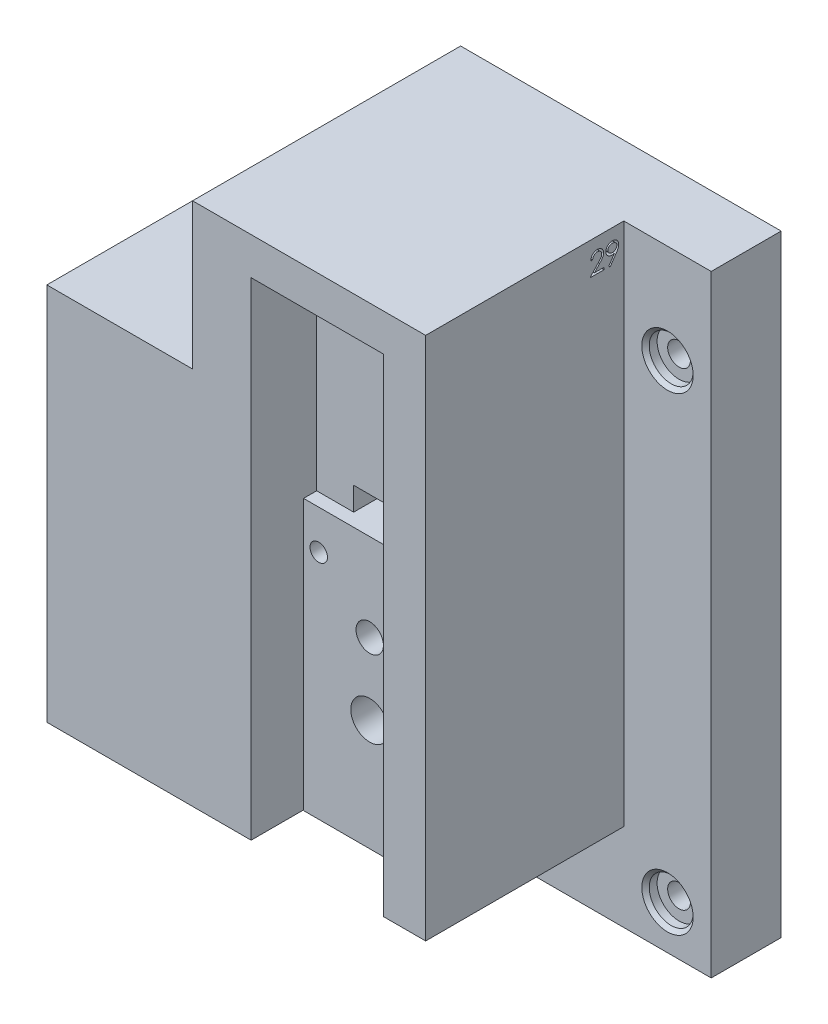
SolidWorks part; units mm, degrees
ref_plane "Front Plane" through (0, 0, 0) normal (0, 0, 1) x (1, 0, 0)
ref_plane "Top Plane" through (0, 0, 0) normal (0, 1, 0) x (1, 0, 0)
ref_plane "Right Plane" through (0, 0, 0) normal (1, 0, 0) x (0, 0, -1)
sketch "Sketch1" plane through (0, 0, 0) normal (0, 0, 1) x (1, 0, 0)
  line L1 (0, 0) -> (-65, 0)
  line L2 (0, 0) -> (0, -85)
  line L3 (0, -85) -> (-65, -85)
  line L4 (-65, 0) -> (-65, -85)
  dimension "D1" = 65
  dimension "D2" = 85
extrude "Boss-Extrude1" add sketch "Sketch1" along normal blind 46
sketch "Sketch2" plane through (0, 0, 46) normal (0, 0, 1) x (1, 0, 0)
  line L1 (-65, 0) -> (-40, 0)
  line L2 (-65, 0) -> (-65, -20)
  line L3 (-65, -20) -> (-40, -20)
  line L4 (-40, 0) -> (-40, -20)
  dimension "D1" = 25
  dimension "D2" = 20
extrude "Cut-Extrude1" cut sketch "Sketch2" against normal blind 46
sketch "Sketch3" plane through (0, 0, 0) normal (0, 0, -1) x (-1, 0, 0)
  line L0 (0, 0) -> (-12.6927, 0) construction
  line L1 (7.25, -1.4) -> (29.95, -1.4)
  line L2 (7.25, -1.4) -> (7.25, -83.6)
  line L3 (7.25, -83.6) -> (29.95, -83.6)
  line L4 (29.95, -1.4) -> (29.95, -83.6)
  line L5 (0, -85) -> (-40.2138, -85) construction
  line L7 (0, 0) -> (0, 18.8306) construction
  line L8 (40, 0) -> (40, 20.415) construction
  dimension "D1" = 22.7
  dimension "D2" = 82.2
  dimension "D3" = 2.8
  dimension "D4" = 14.5
extrude "Cut-Extrude2" cut sketch "Sketch3" against normal blind 43.2
sketch "Sketch4" plane through (0, 0, 43.2) normal (0, 0, -1) x (-1, 0, 0)
  line L0 (7.25, -83.6) -> (29.95, -83.6) construction
  line L1 (32.75, -1.4) -> (32.75, 6.5075) construction
  line L2 (32.75, -1.4) -> (54.2037, -1.4) construction
  line L3 (20, -65.9) -> (20, -109.1767) construction
  line L6 (7.25, -1.4) -> (7.25, -83.6) construction
  line L7 (11.25, -21.4049) -> (11.25, -31.9502) construction
  line L8 (7.25, -1.4) -> (7.25, -83.6) construction
  line L11 (25.95, -17.2988) -> (25.95, -39.3226) construction
  line L12 (29.95, -83.6) -> (29.95, -1.4) construction
  line L13 (7.25, -83.6) -> (-10.7411, -83.6) construction
  line L14 (7.25, -1.4) -> (7.25, 5.7136) construction
  line L15 (16.5, -29.53) -> (23.5, -29.53)
  line L16 (16.5, -29.53) -> (16.5, -34.33)
  line L17 (16.5, -34.33) -> (23.5, -34.33)
  line L18 (23.5, -29.53) -> (23.5, -34.33)
  circle A0 centre (20, -65.9) radius 3.25
  circle A1 centre (20, -53.6) radius 2.35
  circle A2 centre (11.25, -45.3) radius 1.5
  circle A3 centre (25.95, -45.3) radius 1.5
  point P4 (18.6, -83.6)
  dimension "D2" = 6.5
  dimension "D4" = 4.7
  dimension "D3" = 12.75
  dimension "D9" = 38.3
  dimension "D10" = 3
  dimension "D11" = 3
  dimension "D1" = 17.7
  dimension "D5" = 30
  dimension "D6" = 4
  dimension "D7" = 4
  dimension "D8" = 38.3
  dimension "D12" = 4.8
  dimension "D13" = 7
  dimension "D14" = 28.13
  dimension "D15" = 3.5
extrude "Cut-Extrude3" cut sketch "Sketch4" against normal blind 29
sketch "Sketch5" plane through (0, 0, 43.2) normal (0, 0, -1) x (-1, 0, 0)
  line L0 (7.25, -83.6) -> (-14.1319, -83.6) construction
  line L1 (7.25, -38.6) -> (29.95, -38.6)
  line L2 (7.25, -1.4) -> (7.25, -83.6) construction
  line L3 (29.95, -83.6) -> (29.95, -1.4) construction
  line L4 (29.95, -38.6) -> (29.95, -1.4)
  line L5 (29.95, -1.4) -> (7.25, -1.4)
  line L6 (7.25, -1.4) -> (7.25, -38.6)
  dimension "D1" = 45
extrude "Cut-Extrude4" cut sketch "Sketch5" against normal blind 2.25
sketch "Sketch7" plane through (0, -20, 0) normal (0, 1, 0) x (1, 0, 0)
  line L0 (-65, -46) -> (-40, -46) construction
  line L1 (-52.5, -11) -> (-52.5, -59.2787) construction
  line L2 (-65, 0) -> (-65, 6.9768) construction
  line L3 (-40, 0) -> (-40, 6.5953) construction
  circle A0 centre (-52.5, -11) radius 3.1
  dimension "D1" = 6.2
  dimension "D2" = 35
  dimension "D3" = 12.5
extrude "Cut-Extrude5" cut sketch "Sketch7" against normal blind 10
sketch "Sketch10" plane through (-65, 0, 0) normal (-1, 0, 0) x (0, 0, 1)
  line L0 (46, -85) -> (0, -85) construction
  line L1 (0, -20) -> (12, -20)
  line L2 (0, -20) -> (0, -85)
  line L3 (0, -85) -> (12, -85)
  line L4 (12, -20) -> (12, -85)
  dimension "D1" = 12
extrude "Boss-Extrude3" add sketch "Sketch10" along normal blind 15
sketch "Sketch11" plane through (-65, 0, 0) normal (-1, 0, 0) x (0, 0, 1)
  circle A0 centre (35, -65) radius 3.2
  dimension "D1" = 6.4
extrude "Cut-Extrude6" cut sketch "Sketch11" against normal blind 20
sketch "Sketch12" plane through (0, -20, 0) normal (0, 1, 0) x (1, 0, 0)
  line L0 (-52.5, -11) -> (-52.5, -49.19) construction
  line L2 (-65, -46) -> (-40, -46) construction
  circle A1 centre (-52.5, -35) radius 3.15
  dimension "D1" = 6.3
  dimension "D2" = 11
extrude "Cut-Extrude7" cut sketch "Sketch12" against normal blind 10
sketch "Sketch13" plane through (0, -20, 0) normal (0, 1, 0) x (1, 0, 0)
  circle A0 centre (-52.5, -11) radius 3.1
extrude "Boss-Extrude5" add sketch "Sketch13" against normal blind 10
sketch "Sketch14" plane through (0, -85, 0) normal (0, -1, 0) x (1, 0, 0)
  line L1 (-80, 12) -> (0, 12)
  line L2 (-80, 12) -> (-80, 0)
  line L3 (-80, 0) -> (0, 0)
  line L4 (0, 12) -> (0, 0)
extrude "Boss-Extrude6" add sketch "Sketch14" along normal blind 15
sketch "Sketch15" plane through (0, 0, 0) normal (1, 0, 0) x (0, 0, -1)
  line L0 (-12, -85) -> (-12, 8.9714) construction
  line L2 (0, 0) -> (-12, 0)
  line L3 (0, 0) -> (0, -100)
  line L4 (0, -100) -> (-12, -100)
  line L5 (-12, 0) -> (-12, -100)
extrude "Boss-Extrude8" add sketch "Sketch15" along normal blind 15
sketch "Sketch16" plane through (0, 0, 12) normal (0, 0, 1) x (1, 0, 0)
  line L0 (-65, -85) -> (-65, -100) construction
  line L1 (15, -100) -> (-80, -100) construction
  line L3 (-65, -100) -> (-80, -100)
  line L4 (-65, -100) -> (-65, -20)
  line L5 (-65, -20) -> (-80, -20)
  line L6 (-80, -100) -> (-80, -20)
extrude "Cut-Extrude8" cut sketch "Sketch16" against normal blind 15
sketch "Sketch17" plane through (0, 0, 12) normal (0, 0, 1) x (1, 0, 0)
  line L0 (0, -85) -> (15, -100) construction
  line L1 (7.5, -92.5) -> (7.5, 0) construction
  line L2 (15, 0) -> (0, 0) construction
  line L3 (7.5, -92.5) -> (-65, -92.5) construction
  line L4 (-65, -100) -> (-65, -85) construction
  circle A0 centre (7.5, -92.5) radius 3.25
  circle A1 centre (-53, -92.5) radius 3.25
  circle A2 centre (7.5, -12) radius 3.25
  dimension "D1" = 6.5
  dimension "D2" = 6.5
  dimension "D4" = 6.5
  dimension "D3" = 12
  dimension "D5" = 12
hole_wizard "CBORE for #5 Binding Head Machine Screw1" positions "Sketch18" profile "Sketch19" counterbore size "#5" standard "ANSI Inch" end condition through all
sketch "Sketch18" plane through (0, 0, 12) normal (0, 0, 1) x (1, 0, 0)
  point P0 (7.5, -12)
  point P3 (7.5, -92.5)
  point P6 (-53, -92.5)
sketch "Sketch19" plane through (7.5, -12, 12) normal (1, 0, 0) x (0, -1, 0)
  line L0 (0, 0) -> (0, 12)
  line L1 (0, 12) -> (1.9558, 12)
  line L3 (1.9558, 12) -> (1.9558, 1.9812)
  line L4 (3.7706, 1.9812) -> (1.9558, 1.9812)
  line L5 (3.7706, 1.9812) -> (3.7706, 0.635)
  line L6 (3.7706, 0.635) -> (4.4056, 0)
  line L7 (4.4056, 0) -> (0, 0)
  line L8 (-3.7706, 0.635) -> (-4.4056, 0) construction
  line L11 (0, -6.35) -> (0, 107.95) construction
  dimension "Thru Hole Dia." = 3.9116
  dimension "Thru Hole Depth" = 12
  dimension "C'Bore Dia." = 7.5413
  dimension "C'Bore Depth" = 1.9812
  dimension "Near C'Sink Dia." = 8.8113
  dimension "Near C'Sink Angle" = 90
sketch "Sketch20" plane through (0, -20, 0) normal (0, 1, 0) x (1, 0, 0)
  circle A0 centre (-52.5, -35) radius 3.15
extrude "Boss-Extrude9" add sketch "Sketch20" against normal blind 10
sketch "Sketch24" plane through (0, -83.6, 0) normal (0, 1, 0) x (1, 0, 0)
  line L1 (-29.95, -43.2) -> (-7.25, -43.2)
  line L2 (-29.95, -43.2) -> (-29.95, 0)
  line L3 (-29.95, 0) -> (-7.25, 0)
  line L4 (-7.25, -43.2) -> (-7.25, 0)
extrude "Cut-Extrude10" cut sketch "Sketch24" against normal blind 1.5 contours L2 L1 L4 L3
sketch "Sketch28" plane through (0, 0, 43.2) normal (0, 0, -1) x (-1, 0, 0)
  line L1 (7.25, -1.4) -> (29.95, -1.4)
  line L2 (7.25, -1.4) -> (7.25, -85)
  line L3 (7.25, -85) -> (29.95, -85)
  line L4 (29.95, -1.4) -> (29.95, -85)
extrude "Cut-Extrude14" cut sketch "Sketch28" against normal blind 20
sketch "Sketch29" plane through (0, 0, 0) normal (0, 1, 0) x (1, 0, 0)
  line L0 (-40, 0) -> (15, 0)
  line L1 (15, 0) -> (15, -12)
  line L2 (15, -12) -> (0, -12)
  line L3 (0, -12) -> (0, -46)
  line L4 (0, -46) -> (-40, -46)
  line L5 (-40, -46) -> (-40, 0)
extrude "Boss-Extrude10" add sketch "Sketch29" along normal blind 5
sketch "Sketch30" plane through (0, 0, 0) normal (0, 0, 1) x (1, 0, 0)
  line L0 (-29.95, -85.1) -> (-7.25, -85.1)
  line L1 (-29.95, -1.4) -> (-7.25, -1.4)
  line L5 (-7.25, -85.1) -> (-7.25, -1.4)
  line L6 (-29.95, -1.4) -> (-29.95, -85.1)
extrude "Boss-Extrude11" add sketch "Sketch30" along normal blind 37
sketch "Sketch32" plane through (0, 0, 37) normal (0, 0, 1) x (1, 0, 0)
  line L0 (-18.6, -85) -> (-18.6, -1.4) construction
  line L2 (-7.25, -1.4) -> (-29.95, -1.4) construction
  line L4 (-18.6, -53.7) -> (-46.8835, -53.7) construction
  line L5 (-29.95, -85) -> (-7.25, -85) construction
  circle A0 centre (-18.6, -66) radius 3.25
  circle A1 centre (-18.6, -53.7) radius 2.35
  circle A2 centre (-27.35, -45.4) radius 1.5
  circle A3 centre (-9.85, -45.4) radius 1.5
  dimension "D1" = 6.5
  dimension "D4" = 4.7
  dimension "D5" = 3
  dimension "D6" = 3
  dimension "D2" = 19
  dimension "D3" = 12.3
  dimension "D7" = 8.75
  dimension "D8" = 8.75
  dimension "D9" = 8.3
  dimension "D10" = 8.3
extrude "Cut-Extrude15" cut sketch "Sketch32" against normal blind 53.45
sketch "Sketch33" plane through (0, 0, 37) normal (0, 0, 1) x (1, 0, 0)
  line L0 (-29.95, -38.7) -> (-7.25, -38.7)
  line L1 (-29.95, -1.4) -> (-29.95, -85) construction
  line L2 (-7.25, -1.4) -> (-7.25, -85) construction
  line L3 (-29.95, -85.1) -> (-7.25, -85.1) construction
  line L4 (-29.95, -38.7) -> (-29.95, -1.4)
  line L5 (-29.95, -1.4) -> (-7.25, -1.4)
  line L6 (-7.25, -1.4) -> (-7.25, -38.7)
  dimension "D1" = 46.4
extrude "Cut-Extrude16" cut sketch "Sketch33" against normal blind 2.25
sketch "Sketch34" plane through (0, 0, 34.75) normal (0, 0, 1) x (1, 0, 0)
  line L0 (-23.6, -34.7) -> (-18.6, -34.7)
  line L5 (-18.6, -51.35) -> (-18.6, -1.4) construction
  line L6 (-7.25, -1.4) -> (-29.95, -1.4) construction
  line L7 (-29.95, -38.7) -> (-7.25, -38.7) construction
  line L8 (-18.6, -34.7) -> (-13.6, -34.7)
  line L9 (-23.6, -34.7) -> (-23.6, -38.7)
  line L10 (-23.6, -38.7) -> (-13.6, -38.7)
  line L11 (-13.6, -34.7) -> (-13.6, -38.7)
  circle A0 centre (-18.6, -53.7) radius 2.35 construction
  dimension "D1" = 5
  dimension "D2" = 5
  dimension "D3" = 4
extrude "Cut-Extrude17" cut sketch "Sketch34" against normal blind 62.25
sketch "Sketch35" plane through (0, 0, 12) normal (0, 0, 1) x (1, 0, 0)
  line L0 (-65, -85) -> (15, -85)
  line L1 (15, 5) -> (15, -100) construction
  line L2 (15, -85) -> (15, -100)
  line L3 (15, -100) -> (-65, -100)
  line L4 (-65, -100) -> (-65, -85)
sketch "Sketch36" plane through (15, 0, 0) normal (1, 0, 0) x (0, 0, -1)
  line L1 (-12, -85) -> (-28.5288, -85)
  line L2 (-12, -85) -> (-12, -89.1821)
  line L3 (-12, -89.1821) -> (-28.5288, -89.1821)
  line L4 (-28.5288, -85) -> (-28.5288, -89.1821)
extrude "Cut-Extrude22" cut sketch "Sketch36" against normal blind 60
sketch "Sketch37" plane through (0, 0, 0) normal (1, 0, 0) x (0, 0, -1)
  text T0 "29"
extrude "Cut-Extrude23" cut sketch "Sketch37" against normal blind 2
